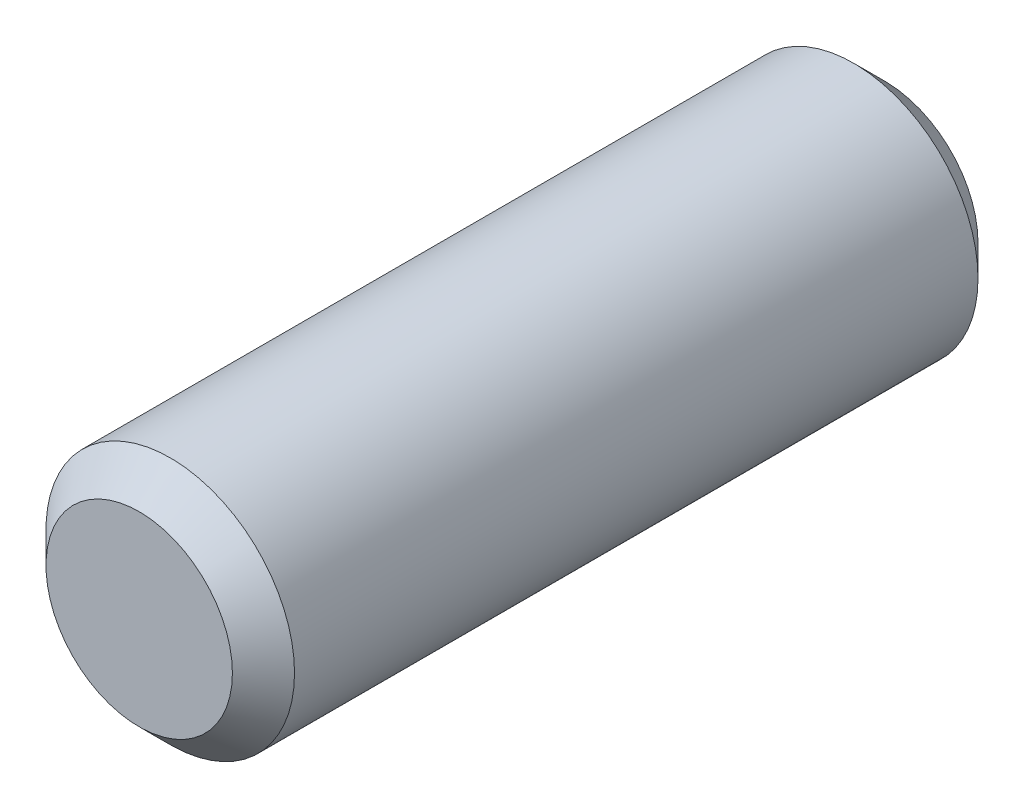
SolidWorks part; units mm, degrees
ref_plane "Plan de face" through (0, 0, 0) normal (0, 0, 1) x (1, 0, 0)
ref_plane "Plan de dessus" through (0, 0, 0) normal (0, 1, 0) x (1, 0, 0)
ref_plane "Plan de droite" through (0, 0, 0) normal (1, 0, 0) x (0, 0, -1)
sketch "Esquisse1" plane through (0, 0, 0) normal (0, 0, 1) x (1, 0, 0)
  circle A0 centre (0, 0) radius 2
  dimension "D1" = 4
extrude "Boss.-Extru.1" add sketch "Esquisse1" along normal mid plane 12
chamfer "Chanfrein1" distance 0.5 angle 45 2 edges at (2, 0, -6) (2, 0, 6)
